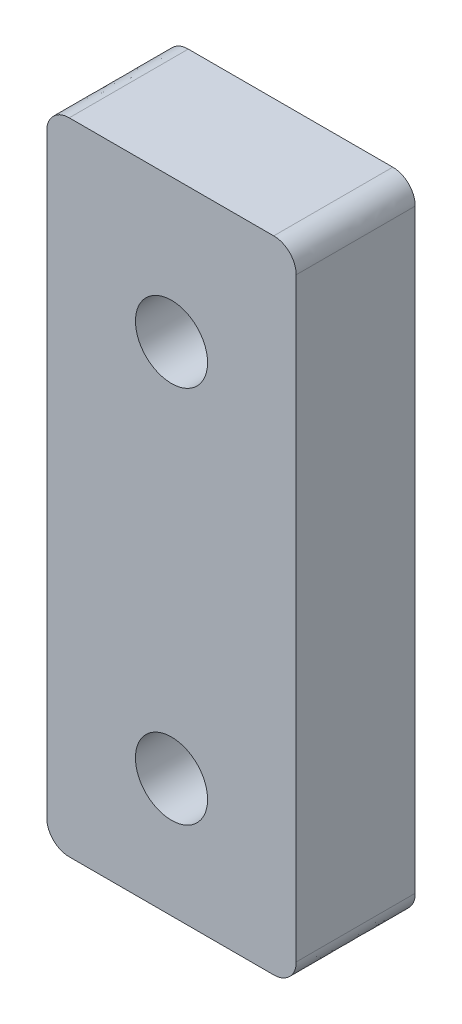
SolidWorks part; units mm, degrees
ref_plane "Front Plane" through (0, 0, 0) normal (0, 0, 1) x (1, 0, 0)
ref_plane "Top Plane" through (0, 0, 0) normal (0, 1, 0) x (1, 0, 0)
ref_plane "Right Plane" through (0, 0, 0) normal (1, 0, 0) x (0, 0, -1)
sketch "Model" plane through (0, 0, 0) normal (0, 0, 1) x (1, 0, 0)
  line L193 (-255.7004, 141.5182) -> (-244.7908, 141.5182)
  line L194 (-243.5919, 140.3197) -> (-243.5919, 108.5737)
  line L195 (-244.7908, 107.3747) -> (-255.7004, 107.3747)
  line L196 (-256.8997, 108.5737) -> (-256.8997, 140.3197)
  circle A0 centre (-250.245, 133.8944) radius 1.9243
  circle A1 centre (-250.245, 113.7165) radius 1.9251
  spline S412 degree 3 poles (-244.7908, 141.5182) (-244.1268, 141.5182) (-243.5919, 140.9838) (-243.5919, 140.3197) knots 0.111111 0.111111 0.111111 0.111111 0.222222 0.222222 0.222222 0.222222
  spline S413 degree 3 poles (-243.5919, 108.5737) (-243.5919, 107.9096) (-244.1268, 107.3747) (-244.7908, 107.3747) knots 0.333333 0.333333 0.333333 0.333333 0.444444 0.444444 0.444444 0.444444
  spline S414 degree 3 poles (-255.7004, 107.3747) (-256.3648, 107.3747) (-256.8997, 107.9096) (-256.8997, 108.5737) knots 0.555556 0.555556 0.555556 0.555556 0.666667 0.666667 0.666667 0.666667
  spline S415 degree 3 poles (-256.8997, 140.3197) (-256.8997, 140.9838) (-256.3648, 141.5182) (-255.7004, 141.5182) knots 0.777778 0.777778 0.777778 0.777778 1 1 1 1
extrude "Boss-Extrude1" add sketch "Model" along normal blind 6.35
